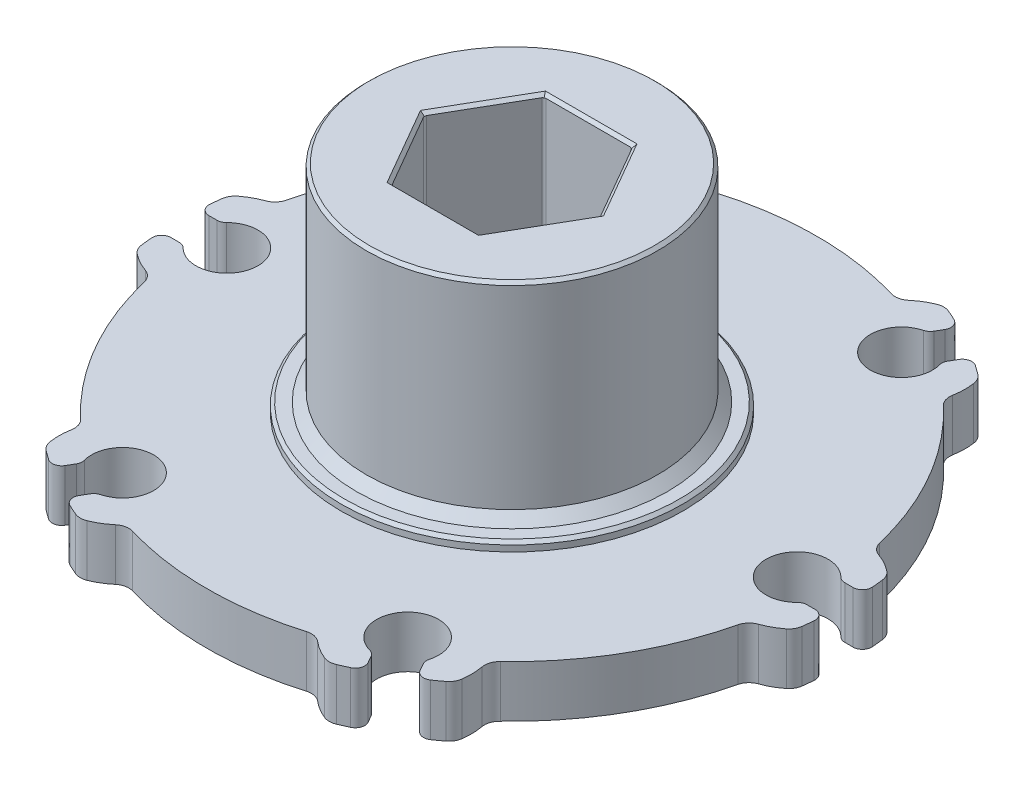
SolidWorks part; units mm, degrees
material "6063-T1"
ref_plane "Front Plane" through (0, 0, 0) normal (0, 0, 1) x (1, 0, 0)
ref_plane "Top Plane" through (0, 0, 0) normal (0, 1, 0) x (1, 0, 0)
ref_plane "Right Plane" through (0, 0, 0) normal (1, 0, 0) x (0, 0, -1)
sketch "Sketch1" plane through (0, 0, 0) normal (0, 1, 0) x (1, 0, 0)
  line L0 (-15.2459, -23.2317) -> (-14.3048, -21.6016)
  line L1 (-11.5552, -23.1891) -> (-12.4963, -24.8192)
  line L2 (12.4963, -24.8192) -> (11.5552, -23.1891)
  line L3 (14.3048, -21.6016) -> (15.2459, -23.2317)
  line L4 (27.7422, -1.5875) -> (25.86, -1.5875)
  line L5 (25.86, 1.5875) -> (27.7422, 1.5875)
  line L6 (15.2459, 23.2317) -> (14.3048, 21.6016)
  line L7 (11.5552, 23.1891) -> (12.4963, 24.8192)
  line L8 (-12.4963, 24.8192) -> (-11.5552, 23.1891)
  line L9 (-14.3048, 21.6016) -> (-15.2459, 23.2317)
  line L10 (-27.7422, 1.5875) -> (-25.86, 1.5875)
  line L11 (-25.86, -1.5875) -> (-27.7422, -1.5875)
  line L12 (-23.8125, 0) -> (23.8125, 0) construction
  line L13 (-11.9063, -20.6222) -> (11.9063, 20.6222) construction
  line L14 (-11.9063, 20.6222) -> (11.9063, -20.6222) construction
  arc A0 (-24.9505, -5.2112) -> (-16.9883, -19.0022) centre (0, 0) ccw
  arc A1 (-16.9883, -19.0022) -> (-17.0804, -21.9183) centre (-11.9063, -20.6222) ccw
  arc A2 (-17.0804, -21.9183) -> (-15.2459, -23.2317) centre (0, 0) ccw
  arc A3 (-14.3048, -21.6016) -> (-11.5552, -23.1891) centre (-11.9063, -20.6222) cw
  arc A4 (-12.4963, -24.8192) -> (-10.4416, -25.7512) centre (0, 0) ccw
  arc A5 (-10.4416, -25.7512) -> (-7.9622, -24.2134) centre (-11.9063, -20.6222) ccw
  arc A6 (-7.9622, -24.2134) -> (7.9622, -24.2134) centre (0, 0) ccw
  arc A7 (7.9622, -24.2134) -> (10.4416, -25.7512) centre (11.9063, -20.6222) ccw
  arc A8 (10.4416, -25.7512) -> (12.4963, -24.8192) centre (0, 0) ccw
  arc A9 (11.5552, -23.1891) -> (14.3048, -21.6016) centre (11.9063, -20.6222) cw
  arc A10 (15.2459, -23.2317) -> (17.0804, -21.9183) centre (0, 0) ccw
  arc A11 (17.0804, -21.9183) -> (16.9883, -19.0022) centre (11.9063, -20.6222) ccw
  arc A12 (16.9883, -19.0022) -> (24.9505, -5.2112) centre (0, 0) ccw
  arc A13 (24.9505, -5.2112) -> (27.522, -3.8329) centre (23.8125, 0) ccw
  arc A14 (27.522, -3.8329) -> (27.7422, -1.5875) centre (0, 0) ccw
  arc A15 (25.86, -1.5875) -> (25.86, 1.5875) centre (23.8125, 0) cw
  arc A16 (27.7422, 1.5875) -> (27.522, 3.8329) centre (0, 0) ccw
  arc A17 (27.522, 3.8329) -> (24.9505, 5.2112) centre (23.8125, 0) ccw
  arc A18 (24.9505, 5.2112) -> (16.9883, 19.0022) centre (0, 0) ccw
  arc A19 (16.9883, 19.0022) -> (17.0804, 21.9183) centre (11.9063, 20.6222) ccw
  arc A20 (17.0804, 21.9183) -> (15.2459, 23.2317) centre (0, 0) ccw
  arc A21 (14.3048, 21.6016) -> (11.5552, 23.1891) centre (11.9063, 20.6222) cw
  arc A22 (12.4963, 24.8192) -> (10.4416, 25.7512) centre (0, 0) ccw
  arc A23 (10.4416, 25.7512) -> (7.9622, 24.2134) centre (11.9063, 20.6222) ccw
  arc A24 (7.9622, 24.2134) -> (-7.9622, 24.2134) centre (0, 0) ccw
  arc A25 (-7.9622, 24.2134) -> (-10.4416, 25.7512) centre (-11.9063, 20.6222) ccw
  arc A26 (-10.4416, 25.7512) -> (-12.4963, 24.8192) centre (0, 0) ccw
  arc A27 (-11.5552, 23.1891) -> (-14.3048, 21.6016) centre (-11.9063, 20.6222) cw
  arc A28 (-15.2459, 23.2317) -> (-17.0804, 21.9183) centre (0, 0) ccw
  arc A29 (-17.0804, 21.9183) -> (-16.9883, 19.0022) centre (-11.9063, 20.6222) ccw
  arc A30 (-16.9883, 19.0022) -> (-24.9505, 5.2112) centre (0, 0) ccw
  arc A31 (-24.9505, 5.2112) -> (-27.522, 3.8329) centre (-23.8125, 0) ccw
  arc A32 (-27.522, 3.8329) -> (-27.7422, 1.5875) centre (0, 0) ccw
  arc A33 (-25.86, 1.5875) -> (-25.86, -1.5875) centre (-23.8125, 0) cw
  arc A34 (-27.7422, -1.5875) -> (-27.522, -3.8329) centre (0, 0) ccw
  arc A35 (-27.522, -3.8329) -> (-24.9505, -5.2112) centre (-23.8125, 0) ccw
  circle A36 centre (0, 0) radius 23.8125 construction
  circle A37 centre (0, 0) radius 25.9086 construction
  circle A38 centre (0, 0) radius 27.7876 construction
  point P67 (0, 0)
  dimension "D1" = 51.8173
  dimension "D2" = 55.5752
  dimension "D3" = 47.625
  dimension "D6" = 25.4889
  dimension "D7" = 3.175
  dimension "D8" = 5.334
  dimension "D4" = 60
  dimension "D5" = 60
extrude "Boss-Extrude1" add sketch "Sketch1" against normal blind 4.318
sketch "Sketch2" plane through (0, 0, 0) normal (0, 1, 0) x (-1, 0, 0)
  circle A0 centre (0, 0) radius 14.2748
  dimension "D1" = 28.5496
extrude "Boss-Extrude2" add sketch "Sketch2" along normal blind 0.762
sketch "Sketch3" plane through (0, 0.762, 0) normal (0, 1, 0) x (-1, 0, 0)
  circle A0 centre (0, 0) radius 12.1666
  dimension "D1" = 24.3332
extrude "Boss-Extrude3" add sketch "Sketch3" along normal blind 17.272
sketch "Sketch4" plane through (0, -4.318, 0) normal (0, -1, 0) x (1, 0, 0)
  circle A0 centre (0, 0) radius 14.2748
  dimension "D1" = 28.5496
extrude "Boss-Extrude4" add sketch "Sketch4" along normal blind 1.524
sketch "Sketch5" plane through (0, -5.842, 0) normal (0, -1, 0) x (1, 0, 0)
  circle A0 centre (0, 0) radius 9.2382
  dimension "D1" = 18.4765
extrude "Boss-Extrude5" add sketch "Sketch5" along normal blind 1.524
sketch "Sketch6" plane through (0, -7.366, 0) normal (0, -1, 0) x (1, 0, 0)
  line L7 (7.347, 0) -> (3.6735, 6.3627)
  line L8 (3.6735, 6.3627) -> (-3.6735, 6.3627)
  line L9 (-3.6735, 6.3627) -> (-7.347, 0)
  line L10 (-7.347, 0) -> (-3.6735, -6.3627)
  line L11 (-3.6735, -6.3627) -> (3.6735, -6.3627)
  line L12 (3.6735, -6.3627) -> (7.347, 0)
  circle A0 centre (0, 0) radius 6.3627 construction
  dimension "D2" = 14.694
extrude "Cut-Extrude1" cut sketch "Sketch6" against normal through all
chamfer "Chamfer1" distance 0.254 angle 45 16 edges at (0, 0.762, 14.2748) (0, -5.842, -14.2748) (0, -7.366, -9.2382) (0, 18.034, 12.1666) (-5.5103, -7.366, -3.1813) (-5.5103, -7.366, 3.1813) (0, -7.366, 6.3627) (5.5103, -7.366, 3.1813) (5.5103, -7.366, -3.1813) (0, -7.366, -6.3627) (5.5103, 18.034, -3.1813) (5.5103, 18.034, 3.1813) (0, 18.034, 6.3627) (-5.5103, 18.034, 3.1813) (-5.5103, 18.034, -3.1813) (0, 18.034, -6.3627)
chamfer "Chamfer2" distance 0.8128 angle 45 1 edges at (0, 0.762, 12.1666)
fillet "Fillet1" radius 0.254 7 edges at (-7.347, 5.334, 0) (-3.6735, 5.334, 6.3627) (7.347, 5.334, 0) (3.6735, 5.334, 6.3627) (0, -4.318, 14.2748) (3.6735, 5.334, -6.3627) (-3.6735, 5.334, -6.3627)
fillet "Fillet2" radius 0.7874 24 edges at (-27.7422, -2.159, -1.5875) (-14.3048, -2.159, 21.6016) (12.4963, -2.159, 24.8192) (-11.5552, -2.159, 23.1891) (11.5552, -2.159, -23.1891) (12.4963, -2.159, -24.8192) (-14.3048, -2.159, -21.6016) (-15.2459, -2.159, 23.2317) (-25.86, -2.159, 1.5875) (11.5552, -2.159, 23.1891) (14.3048, -2.159, -21.6016) (14.3048, -2.159, 21.6016) (27.7422, -2.159, -1.5875) (-12.4963, -2.159, 24.8192) (-11.5552, -2.159, -23.1891) (-12.4963, -2.159, -24.8192) (-27.7422, -2.159, 1.5875) (25.86, -2.159, 1.5875) (-25.86, -2.159, -1.5875) (25.86, -2.159, -1.5875) (15.2459, -2.159, 23.2317) (-15.2459, -2.159, -23.2317) (27.7422, -2.159, 1.5875) (15.2459, -2.159, -23.2317)
fillet "Fillet3" radius 1.27 24 edges at (16.9883, -2.159, 19.0022) (-24.9505, -2.159, 5.2112) (7.9622, -2.159, -24.2134) (-10.4416, -2.159, 25.7512) (-7.9622, -2.159, 24.2134) (10.4416, -2.159, 25.7512) (24.9505, -2.159, -5.2112) (17.0804, -2.159, 21.9183) (-16.9883, -2.159, -19.0022) (27.522, -2.159, 3.8329) (-16.9883, -2.159, 19.0022) (27.522, -2.159, -3.8329) (7.9622, -2.159, 24.2134) (17.0804, -2.159, -21.9183) (24.9505, -2.159, 5.2112) (10.4416, -2.159, -25.7512) (16.9883, -2.159, -19.0022) (-10.4416, -2.159, -25.7512) (-7.9622, -2.159, -24.2134) (-17.0804, -2.159, -21.9183) (-24.9505, -2.159, -5.2112) (-27.522, -2.159, -3.8329) (-27.522, -2.159, 3.8329) (-17.0804, -2.159, 21.9183)
